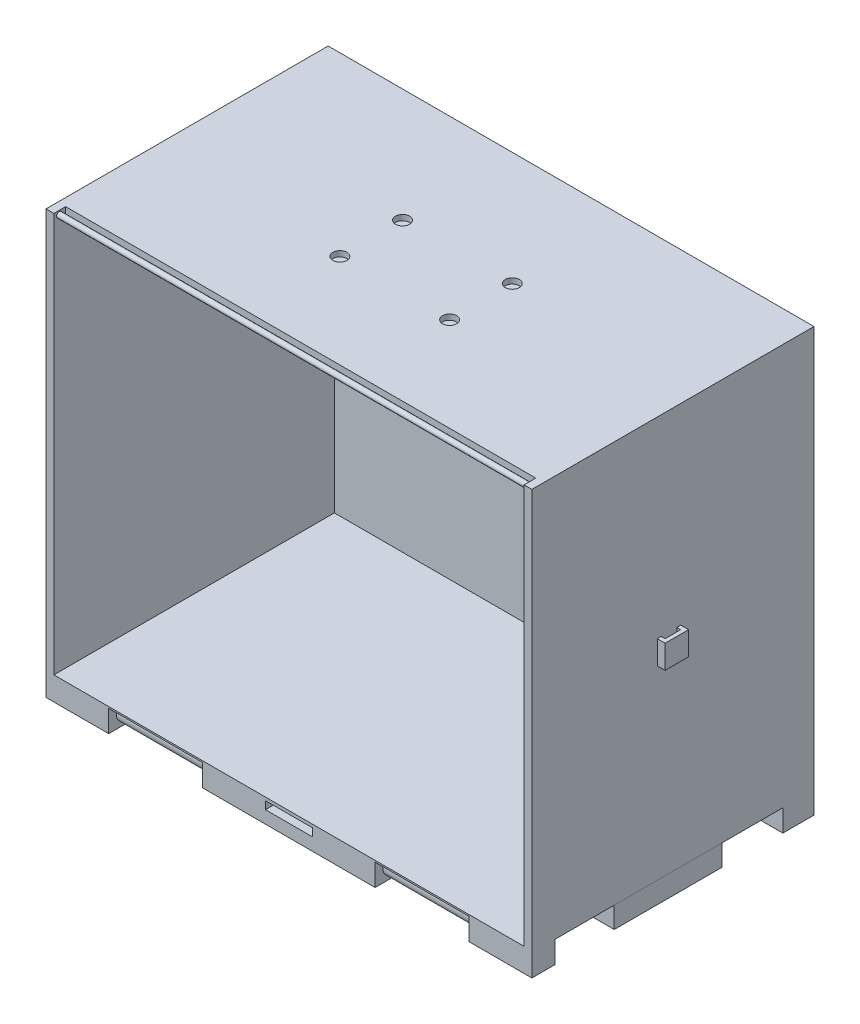
SolidWorks part; units mm, degrees
material "Polyetheretherketone (PEEK)"
ref_plane "Front Plane" through (0, 0, 0) normal (0, 0, 1) x (1, 0, 0)
ref_plane "Top Plane" through (0, 0, 0) normal (0, 1, 0) x (1, 0, 0)
ref_plane "Right Plane" through (0, 0, 0) normal (1, 0, 0) x (0, 0, -1)
sketch "Sketch1" plane through (0, 0, 0) normal (0, 0, 1) x (1, 0, 0)
  line L1 (-300, 250) -> (300, 250)
  line L2 (-300, 250) -> (-300, -250)
  line L3 (-300, -250) -> (300, -250)
  line L4 (300, 250) -> (300, -250)
  line L5 (-300, 250) -> (300, -250) construction
  line L6 (-300, -250) -> (300, 250) construction
  point P0 (0, 0)
  dimension "D1" = 500
  dimension "D2" = 600
extrude "Boss-Extrude1" add sketch "Sketch1" along normal mid plane 350
shell "Shell1" thickness 10
sketch "Sketch3" plane through (0, -260, 0) normal (0, -1, 0) x (1, 0, 0)
  line L4 (-310, -185) -> (310, -185)
  line L5 (310, -185) -> (310, 175)
  line L6 (310, 175) -> (-310, 175)
  line L7 (-310, 175) -> (-310, -185)
  line L8 (-310, -185) -> (310, -185)
  line L9 (310, -185) -> (310, 175)
  line L10 (310, 175) -> (-310, 175)
  line L11 (-310, 175) -> (-310, -185)
  dimension "D1" = 0
extrude "Boss-Extrude2" add sketch "Sketch3" along normal blind 20
sketch "Sketch5" plane through (0, -280, 0) normal (0, -1, 0) x (1, 0, 0)
  line L0 (310, 175) -> (-310, 175) construction
  line L1 (-230, 25) -> (-110, 25)
  line L2 (-230, 25) -> (-230, 175)
  line L3 (-230, 175) -> (-110, 175)
  line L4 (-110, 25) -> (-110, 175)
  line L5 (-230, 25) -> (-110, 175) construction
  line L6 (-230, 175) -> (-110, 25) construction
  line L7 (-310, 175) -> (-310, -185) construction
  line L8 (0, -201.5973) -> (0, 201.5973) construction
  line L9 (230, 175) -> (110, 25) construction
  line L10 (230, 25) -> (110, 175) construction
  line L11 (110, 25) -> (110, 175)
  line L12 (230, 175) -> (110, 175)
  line L13 (230, 25) -> (230, 175)
  line L14 (230, 25) -> (110, 25)
  line L16 (-280, -260) -> (-280, -110)
  line L17 (280, -110) -> (160, -110)
  line L18 (280, -260) -> (160, -110) construction
  line L19 (-160, -260) -> (-160, -110)
  line L20 (280, -260) -> (280, -110)
  line L21 (-280, -110) -> (-160, -110)
  line L22 (-280, -260) -> (-160, -260)
  line L23 (-280, -260) -> (-160, -110) construction
  line L24 (280, -110) -> (160, -260) construction
  line L25 (160, -260) -> (160, -110)
  line L26 (280, -260) -> (160, -260)
  line L27 (-280, -110) -> (-160, -260) construction
  point P0 (-170, 100)
  point P11 (170, 100)
  point P16 (-220, -185)
  point P21 (220, -185)
  dimension "D1" = 80
  dimension "D2" = 120
  dimension "D3" = 150
extrude "Cut-Extrude1" cut sketch "Sketch5" against normal blind 50
sketch "Sketch8" plane through (0, 0, 0) normal (0, 1, 0) x (1, 0, 0)
  line L0 (-310, 10) -> (-315, 10)
  line L1 (-310, -175) -> (-310, 185) construction
  line L2 (-315, 10) -> (-315, -10)
  line L3 (-315, -10) -> (-310, -10)
  line L4 (-310, 15) -> (-320, 15)
  line L5 (-320, 15) -> (-320, -15)
  line L6 (-320, -15) -> (-310, -15)
  line L7 (-310, 15) -> (-310, 10)
  line L8 (-310, -10) -> (-310, -15)
  point P5 (-315, 0)
  dimension "D1" = 5
  dimension "D2" = 20
  dimension "D3" = 5
extrude "Boss-Extrude3" add sketch "Sketch8" along normal mid plane 30
sketch "Sketch9" plane through (-110, 0, 0) normal (-1, 0, 0) x (0, 0, 1)
  line L0 (25, -280) -> (175, -280) construction
  line L2 (175, -250) -> (175, -280) construction
  line L4 (-185, -280) -> (-110, -280) construction
  line L5 (-185, -230) -> (-185, -280) construction
  circle A0 centre (155, -265) radius 10
  circle A2 centre (-165, -265) radius 10
  circle A3 centre (-165, -265) radius 9.2069
  circle A4 centre (155, -265) radius 8.805
  dimension "D1" = 20
  dimension "D5" = 20
  dimension "D2" = 15
  dimension "D3" = 20
  dimension "D4" = 15
  dimension "D6" = 20
extrude "Boss-Extrude4" add sketch "Sketch9" along normal blind 180
mirror "Mirror1" about plane through (0, 0, 0) normal (1, 0, 0) of "Boss-Extrude3", "Boss-Extrude4"
sketch "Sketch17" plane through (0, 260, 0) normal (0, 1, 0) x (1, 0, 0)
  line L0 (-194.2233, 185) -> (-204.2233, 185)
  line L1 (310, 185) -> (-310, 185) construction
  line L2 (-204.2233, 185) -> (-204.2233, 191.5405)
  line L3 (-204.2233, 191.5405) -> (-159.461, 191.5405)
  line L4 (-159.461, 191.5405) -> (-159.461, 185)
  line L5 (-159.461, 185) -> (-169.461, 185)
  line L6 (-169.461, 185) -> (-169.461, 188.4429)
  line L7 (-169.461, 188.4429) -> (-194.2233, 188.4429)
  line L8 (-194.2233, 188.4429) -> (-194.2233, 185)
  line L9 (0, -201.5973) -> (0, 201.5973) construction
  line L10 (194.2233, 188.4429) -> (194.2233, 185)
  line L11 (169.461, 188.4429) -> (194.2233, 188.4429)
  line L12 (169.461, 185) -> (169.461, 188.4429)
  line L13 (159.461, 185) -> (169.461, 185)
  line L14 (159.461, 191.5405) -> (159.461, 185)
  line L15 (204.2233, 191.5405) -> (159.461, 191.5405)
  line L16 (204.2233, 185) -> (204.2233, 191.5405)
  line L17 (194.2233, 185) -> (204.2233, 185)
  dimension "D1" = 10
  dimension "D2" = 10
extrude "Boss-Extrude8" add sketch "Sketch17" along normal mid plane 20 from surface at -260 starting at plane "Top Plane"
sketch "Sketch147" plane through (0, 260, 0) normal (0, 1, 0) x (1, 0, 0)
  line L0 (-300, -175) -> (-300, -160)
  line L1 (310, -175) -> (-310, -175) construction
  line L2 (-300, -160) -> (300, -160)
  line L3 (300, -160) -> (300, -175)
  line L4 (-310, -175) -> (-310, 185) construction
  line L5 (310, -175) -> (310, 185) construction
  line L6 (-300, -175) -> (300, -175)
  dimension "D1" = 10
  dimension "D2" = 10
  dimension "D3" = 15
extrude "Cut-Extrude2" cut sketch "Sketch147" against normal blind 10
sketch "Sketch148" plane through (-300, 0, 0) normal (1, 0, 0) x (0, 0, -1)
  line L0 (-175, -280) -> (-175, 260) construction
  line L1 (-175, 260) -> (185, 260) construction
  circle A0 centre (-168, 255) radius 3.5
  dimension "D1" = 7
  dimension "D2" = 7
  dimension "D3" = 5
extrude "Boss-Extrude10" add sketch "Sketch148" along normal up to surface (600 mm away) up to face at (300, 86.6667, 53.3333)
sketch "Sketch149" plane through (0, 260, 0) normal (0, 1, 0) x (1, 0, 0)
  line L1 (-50, 50) -> (50, 50) construction
  line L2 (-50, 50) -> (-50, -50) construction
  line L3 (-50, -50) -> (50, -50) construction
  line L4 (50, 50) -> (50, -50) construction
  line L5 (-50, 50) -> (50, -50) construction
  line L6 (-50, -50) -> (50, 50) construction
  circle A0 centre (-70, 40) radius 9
  point P0 (0, 0)
  point P8 (-61, 40)
  point P9 (-70, 49)
  dimension "D3" = 18
  dimension "D1" = 100
  dimension "D2" = 20
  dimension "D4" = 1
extrude "Cut-Extrude3" cut sketch "Sketch149" against normal blind 7
mirror "Mirror3" about plane through (0, 0, 0) normal (0, 0, 1) of "Cut-Extrude3" second plane through (0, 0, 0) second plane normal (1, 0, 0)
sketch "Sketch150" plane through (0, 0, 175) normal (0, 0, 1) x (1, 0, 0)
  line L0 (-300, -250) -> (-280, -250) construction
  line L1 (-30, -254) -> (30, -254)
  line L2 (-30, -254) -> (-30, -264)
  line L3 (-30, -264) -> (30, -264)
  line L4 (30, -254) -> (30, -264)
  line L5 (-30, -254) -> (30, -264) construction
  line L6 (-30, -264) -> (30, -254) construction
  point P0 (0, -259)
  dimension "D1" = 4
  dimension "D2" = 10
  dimension "D3" = 60
extrude "Cut-Extrude4" cut sketch "Sketch150" against normal blind 30
sketch "Sketch154" plane through (0, -280, 0) normal (0, -1, 0) x (1, 0, 0)
  line L0 (231, 174) -> (231, 24)
  line L1 (231, 24) -> (109, 24)
  line L2 (109, 24) -> (109, 174)
  line L3 (109, 174) -> (-109, 174)
  line L4 (-109, 174) -> (-109, 24)
  line L5 (-109, 24) -> (-231, 24)
  line L6 (-231, 24) -> (-231, 174)
  line L7 (-231, 174) -> (-309, 174)
  line L8 (-309, 174) -> (-309, -184)
  line L9 (-309, -184) -> (-281, -184)
  line L10 (-281, -184) -> (-281, -109)
  line L11 (-281, -109) -> (-159, -109)
  line L12 (-159, -109) -> (-159, -184)
  line L13 (-159, -184) -> (159, -184)
  line L14 (159, -184) -> (159, -109)
  line L15 (159, -109) -> (281, -109)
  line L16 (281, -109) -> (281, -184)
  line L17 (281, -184) -> (309, -184)
  line L18 (309, -184) -> (309, 174)
  line L19 (309, 174) -> (231, 174)
  line L20 (230, 175) -> (230, 25)
  line L21 (230, 25) -> (110, 25)
  line L22 (110, 25) -> (110, 175)
  line L23 (110, 175) -> (-110, 175)
  line L24 (-110, 175) -> (-110, 25)
  line L25 (-110, 25) -> (-230, 25)
  line L26 (-230, 25) -> (-230, 175)
  line L27 (-230, 175) -> (-310, 175)
  line L28 (-310, 175) -> (-310, -185)
  line L29 (-310, -185) -> (-280, -185)
  line L30 (-280, -185) -> (-280, -110)
  line L31 (-280, -110) -> (-160, -110)
  line L32 (-160, -110) -> (-160, -185)
  line L33 (-160, -185) -> (160, -185)
  line L34 (160, -185) -> (160, -110)
  line L35 (160, -110) -> (280, -110)
  line L36 (280, -110) -> (280, -185)
  line L37 (280, -185) -> (310, -185)
  line L38 (310, -185) -> (310, 175)
  line L39 (310, 175) -> (230, 175)
  line L40 (230, 175) -> (230, 25)
  line L41 (230, 25) -> (110, 25)
  line L42 (110, 25) -> (110, 175)
  line L43 (110, 175) -> (-110, 175)
  line L44 (-110, 175) -> (-110, 25)
  line L45 (-110, 25) -> (-230, 25)
  line L46 (-230, 25) -> (-230, 175)
  line L47 (-230, 175) -> (-310, 175)
  line L48 (-310, 175) -> (-310, -185)
  line L49 (-310, -185) -> (-280, -185)
  line L50 (-280, -185) -> (-280, -110)
  line L51 (-280, -110) -> (-160, -110)
  line L52 (-160, -110) -> (-160, -185)
  line L53 (-160, -185) -> (160, -185)
  line L54 (160, -185) -> (160, -110)
  line L55 (160, -110) -> (280, -110)
  line L56 (280, -110) -> (280, -185)
  line L57 (280, -185) -> (310, -185)
  line L58 (310, -185) -> (310, 175)
  line L59 (310, 175) -> (230, 175)
  dimension "D1" = 0
  dimension "D2" = 1
sketch "Sketch155" plane through (-310, 0, 0) normal (-1, 0, 0) x (0, 0, 1)
  line L0 (175, -280) -> (-185, -280) construction
  line L1 (-145.2448, -252) -> (145.2448, -252)
  line L2 (-145.2448, -252) -> (-145.2448, -280)
  line L3 (-145.2448, -280) -> (145.2448, -280)
  line L4 (145.2448, -252) -> (145.2448, -280)
  line L5 (-145.2448, -252) -> (145.2448, -280) construction
  line L6 (-145.2448, -280) -> (145.2448, -252) construction
  point P0 (0, -266)
  dimension "D1" = 28
extrude "Cut-Extrude11" cut sketch "Sketch155" against normal through all
sketch "Sketch157" plane through (-230, 0, 0) normal (1, 0, 0) x (0, 0, -1)
  line L0 (-145.2448, -252) -> (-175, -252)
  line L1 (-175, -250) -> (-175, -280) construction
  line L2 (-175, -252) -> (-175, -250)
  line L3 (-175, -250) -> (-25, -250)
  line L4 (-25, -250) -> (-25, -252)
  line L13 (-175, -280) -> (-145.2448, -280)
  line L14 (-145.2448, -280) -> (-145.2448, -267.199)
  line L15 (-145.2448, -262.801) -> (-145.2448, -252)
  line L16 (-145.2448, -252) -> (-25, -252)
  line L17 (-25, -252) -> (-25, -250)
  line L18 (-25, -250) -> (-175, -250)
  line L19 (-175, -250) -> (-175, -280)
  line L24 (-145.2448, -252) -> (-25, -252)
  arc A1 (-145.2448, -262.801) -> (-145.2448, -267.199) centre (-155, -265) ccw
  dimension "D1" = 0
extrude "Boss-Extrude11" add sketch "Sketch157" along normal blind 488
sketch "Sketch159" plane through (160, 0, 0) normal (1, 0, 0) x (0, 0, -1)
  line L0 (145.2448, -252) -> (185, -252)
  line L1 (185, -280) -> (185, 260) construction
  line L2 (145.2448, -252) -> (110, -252)
  line L3 (110, -252) -> (110, -250)
  line L4 (110, -250) -> (175, -250)
  line L5 (175, -250) -> (175, -230)
  line L6 (175, -230) -> (185, -230)
  line L7 (185, -230) -> (185, -252)
extrude "Boss-Extrude12" add sketch "Sketch159" along normal blind 125 and the other way blind 445
sketch "Sketch160" plane through (0, 0, -175) normal (0, 0, 1) x (1, 0, 0)
  line L4 (-300, -250) -> (300, -250)
  line L5 (300, -250) -> (300, 250)
  line L6 (300, 250) -> (-300, 250)
  line L7 (-300, 250) -> (-300, -250)
  line L8 (-300, -250) -> (300, -250)
  line L9 (300, -250) -> (300, 250)
  line L10 (300, 250) -> (-300, 250)
  line L11 (-300, 250) -> (-300, -250)
  dimension "D1" = 0
extrude "Cut-Extrude12" cut sketch "Sketch160" against normal blind 8
sketch "Sketch161" plane through (0, -252, 0) normal (0, -1, 0) x (1, 0, 0)
  line L0 (309, -184) -> (309, 174) construction
  line L1 (-309, -68.8888) -> (309, -68.8888)
  line L2 (-309, -68.8888) -> (-309, 68.8888)
  line L3 (-309, 68.8888) -> (309, 68.8888)
  line L4 (309, -68.8888) -> (309, 68.8888)
  line L5 (-309, -68.8888) -> (309, 68.8888) construction
  line L6 (-309, 68.8888) -> (309, -68.8888) construction
  point P0 (0, 0)
extrude "Boss-Extrude13" add sketch "Sketch161" along normal blind 28
